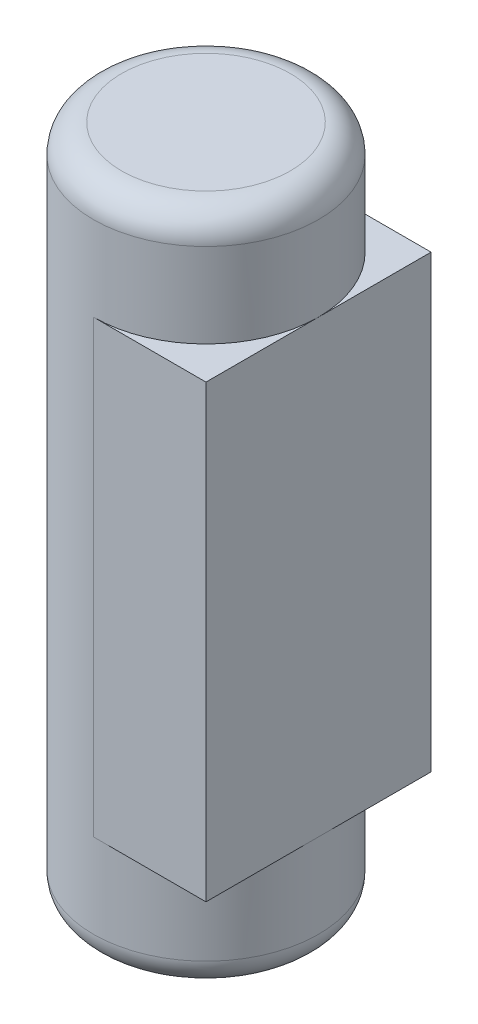
SolidWorks part; units mm, degrees
ref_plane "Front Plane" through (0, 0, 0) normal (0, 0, 1) x (1, 0, 0)
ref_plane "Top Plane" through (0, 0, 0) normal (0, 1, 0) x (1, 0, 0)
ref_plane "Right Plane" through (0, 0, 0) normal (1, 0, 0) x (0, 0, -1)
sketch "Sketch1" plane through (0, 0, 0) normal (0, 1, 0) x (1, 0, 0)
  circle A0 centre (0, 0) radius 50.8
extrude "Boss-Extrude1" add sketch "Sketch1" along normal blind 304.8
sketch "Sketch2" plane through (0, 0, 0) normal (1, 0, 0) x (0, 0, -1)
  line L0 (0, 0) -> (50.8, 0)
  line L1 (-50.8, 0) -> (50.8, 0) construction
  line L3 (50.8, 0) -> (50.8, 304.8) construction
  line L4 (-50.8, 304.8) -> (-50.8, 0) construction
  line L5 (50.8, 50.8) -> (-50.8, 50.8)
  line L6 (50.8, 50.8) -> (50.8, 254)
  line L7 (50.8, 254) -> (-50.8, 254)
  line L8 (-50.8, 50.8) -> (-50.8, 254)
extrude "Boss-Extrude2" add sketch "Sketch2" along normal blind 50.8 contours L6 L5 L8 L7
fillet "Fillet1" radius 12.7 2 edges at (0, 0, 50.8) (0, 304.8, 50.8)
